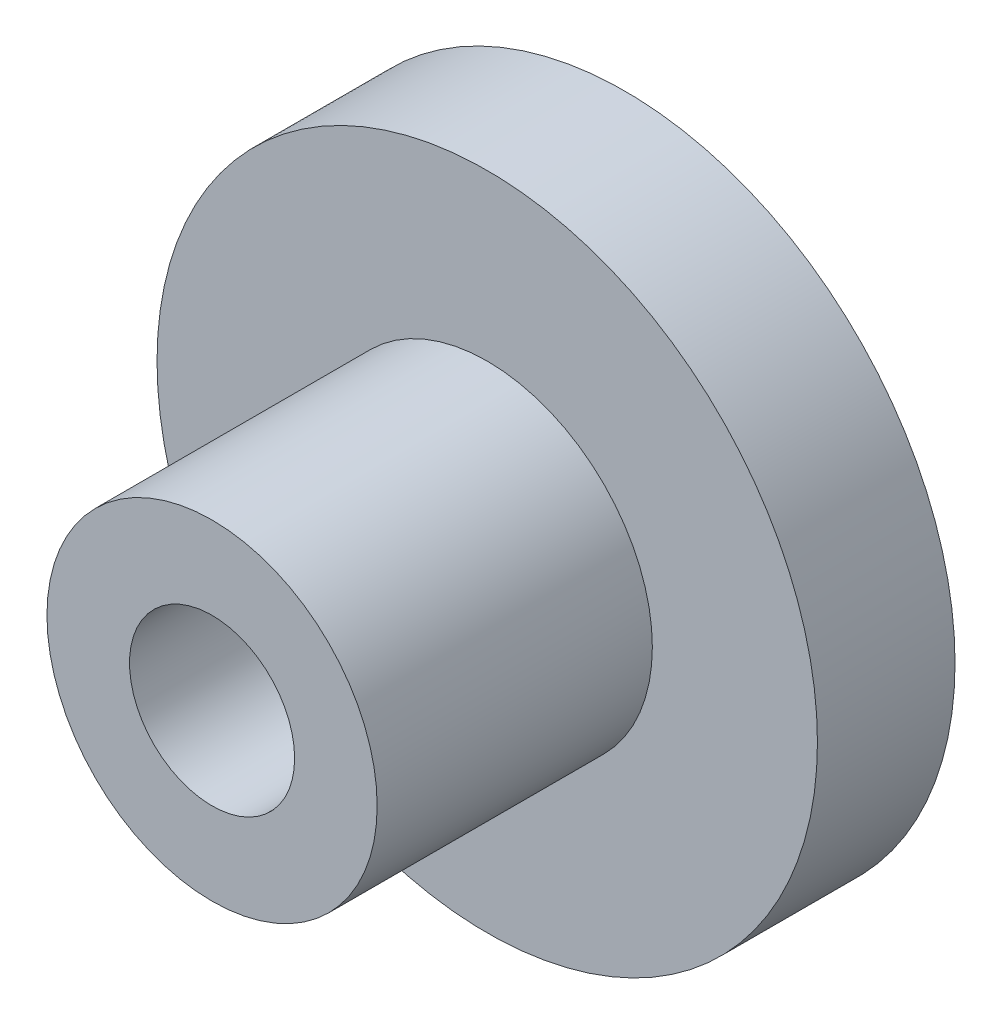
SolidWorks part; units mm, degrees
ref_plane "Front Plane" through (0, 0, 0) normal (0, 0, 1) x (1, 0, 0)
ref_plane "Top Plane" through (0, 0, 0) normal (0, 1, 0) x (1, 0, 0)
ref_plane "Right Plane" through (0, 0, 0) normal (1, 0, 0) x (0, 0, -1)
sketch "Sketch1" plane through (0, 0, 0) normal (0, 0, 1) x (1, 0, 0)
  circle A0 centre (0, 0) radius 6
  dimension "D1" = 12
extrude "Boss-Extrude1" add sketch "Sketch1" along normal blind 2.5
sketch "Sketch2" plane through (0, 0, 2.5) normal (0, 0, 1) x (1, 0, 0)
  circle A0 centre (0, 0) radius 3
  dimension "D1" = 6
extrude "Boss-Extrude2" add sketch "Sketch2" along normal blind 5
sketch "Sketch3" plane through (0, 0, 7.5) normal (0, 0, 1) x (1, 0, 0)
  circle A0 centre (0, 0) radius 1.5
  dimension "D1" = 3
extrude "Cut-Extrude1" cut sketch "Sketch3" against normal through all
